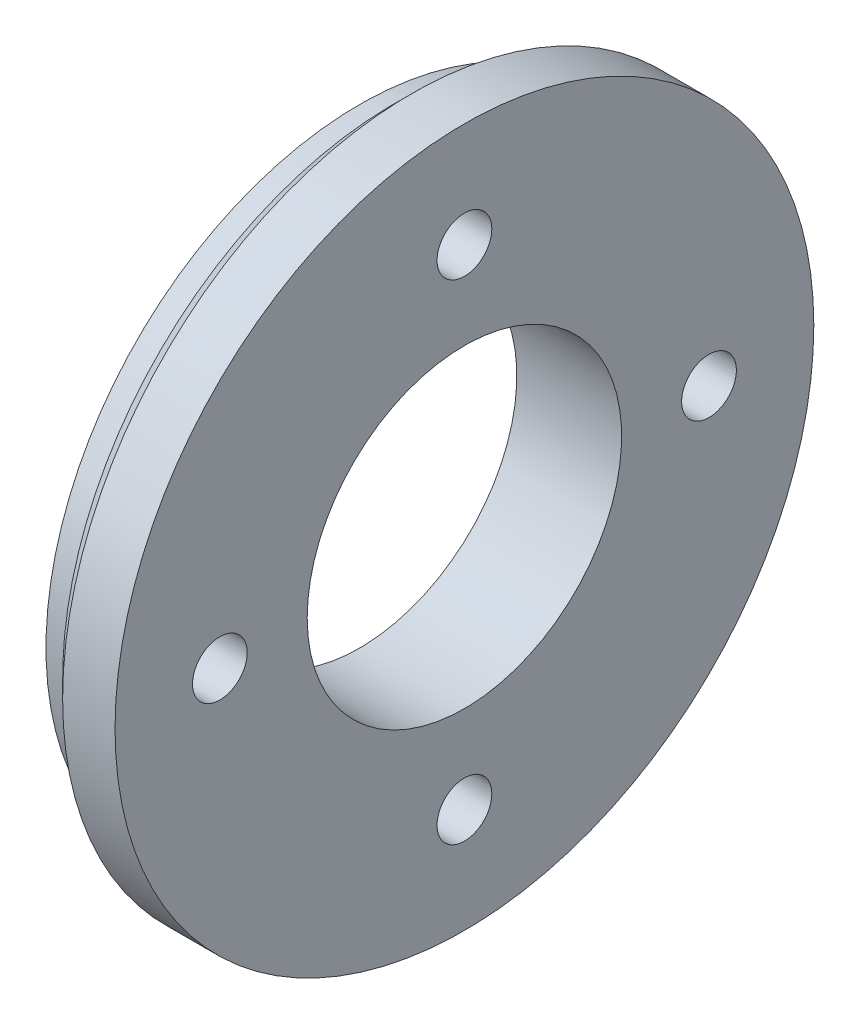
SolidWorks part; units mm, degrees
material "6061-T6 (SS)"
ref_plane "Front Plane" through (0, 0, 0) normal (0, 0, 1) x (1, 0, 0)
ref_plane "Top Plane" through (0, 0, 0) normal (0, 1, 0) x (1, 0, 0)
ref_plane "Right Plane" through (0, 0, 0) normal (1, 0, 0) x (0, 0, -1)
sketch "Sketch1" plane through (0, 0, 0) normal (1, 0, 0) x (0, 0, -1)
  circle A0 centre (0, 0) radius 31.75
  circle A1 centre (0, 0) radius 14.2875
  dimension "D1" = 63.5
  dimension "D2" = 28.575
extrude "Boss-Extrude1" add sketch "Sketch1" along normal mid plane 9.525
sketch "Sketch2" plane through (-4.7625, 0, 0) normal (1, 0, 0) x (0, 0, -1)
  circle A0 centre (0, 0) radius 28.4988
  circle A1 centre (0, 0) radius 31.75
  circle A2 centre (0, 0) radius 31.75 construction
  dimension "D1" = 3.2512
extrude "Cut-Extrude1" cut sketch "Sketch2" along normal blind 3.175
sketch "Sketch3" plane through (4.7625, 0, 0) normal (1, 0, 0) x (0, 0, -1)
  circle A0 centre (0, 0) radius 22.225 construction
  circle A1 centre (0, 22.225) radius 2.4892
  circle A2 centre (-22.225, 0) radius 2.4892
  circle A3 centre (0, -22.225) radius 2.4892
  circle A4 centre (22.225, 0) radius 2.4892
  circle A5 centre (0, 0) radius 14.2875 construction
  dimension "D1" = 4.9784
  dimension "D2" = 7.9375
extrude "Cut-Extrude2" cut sketch "Sketch3" against normal through all
chamfer "Chamfer1" distance 1.5875 angle 45 1 edges at (-1.5875, 0, -31.75)
